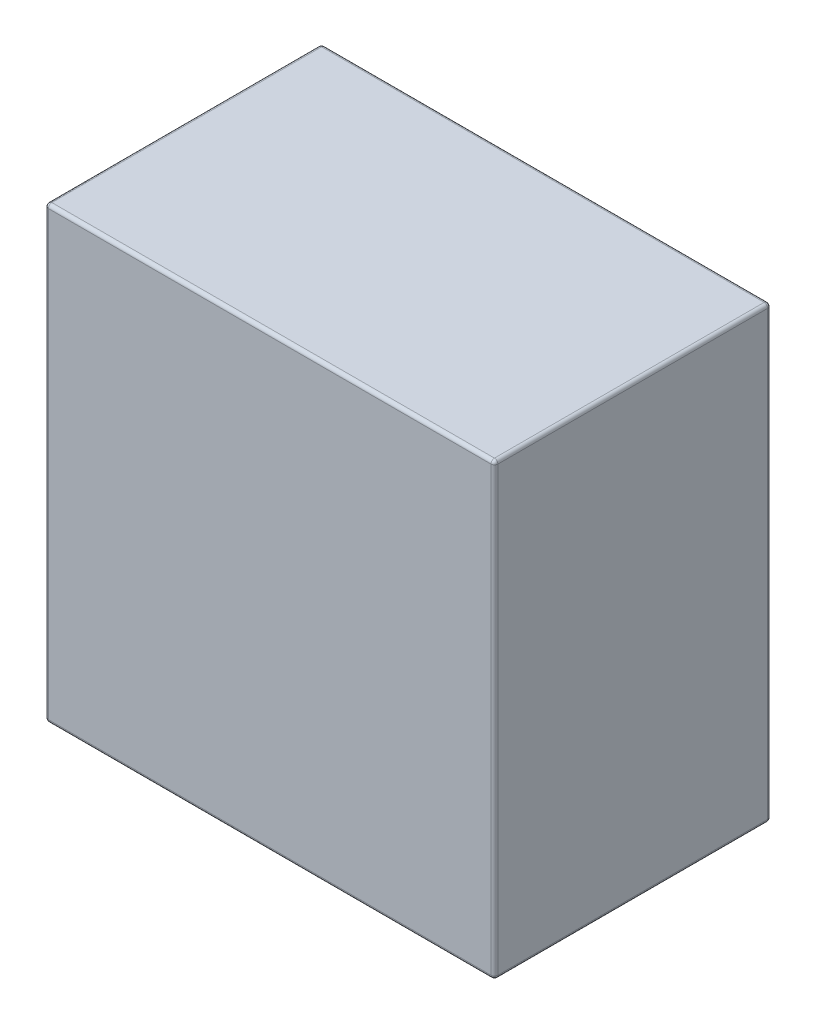
SolidWorks part; units mm, degrees
ref_plane "Front Plane" through (0, 0, 0) normal (1, 0, 0) x (0, 1, 0)
ref_plane "Top Plane" through (0, 0, 0) normal (0, 0, 1) x (0, 1, 0)
ref_plane "Right Plane" through (0, 0, 0) normal (0, 1, 0) x (-1, 0, 0)
sketch "Sketch1" plane through (0, 0, 0) normal (0, 0, 1) x (0, 1, 0)
  line L1 (-6.5, -6.5) -> (6.5, -6.5)
  line L2 (-6.5, -6.5) -> (-6.5, 6.5)
  line L3 (-6.5, 6.5) -> (6.5, 6.5)
  line L4 (6.5, -6.5) -> (6.5, 6.5)
  line L5 (-6.5, -6.5) -> (6.5, 6.5) construction
  line L6 (-6.5, 6.5) -> (6.5, -6.5) construction
  point P0 (0, 0)
  dimension "D1" = 13
  dimension "D2" = 13
extrude "Boss-Extrude1" add sketch "Sketch1" along normal blind 8
fillet "Fillet1" radius 0.1 12 edges at (-6.5, 6.5, 4) (-6.5, -6.5, 4) (6.5, -6.5, 4) (6.5, 6.5, 4) (6.5, 0, 8) (0, -6.5, 8) (-6.5, 0, 8) (0, 6.5, 8) (6.5, 0, 0) (0, -6.5, 0) (-6.5, 0, 0) (0, 6.5, 0)
